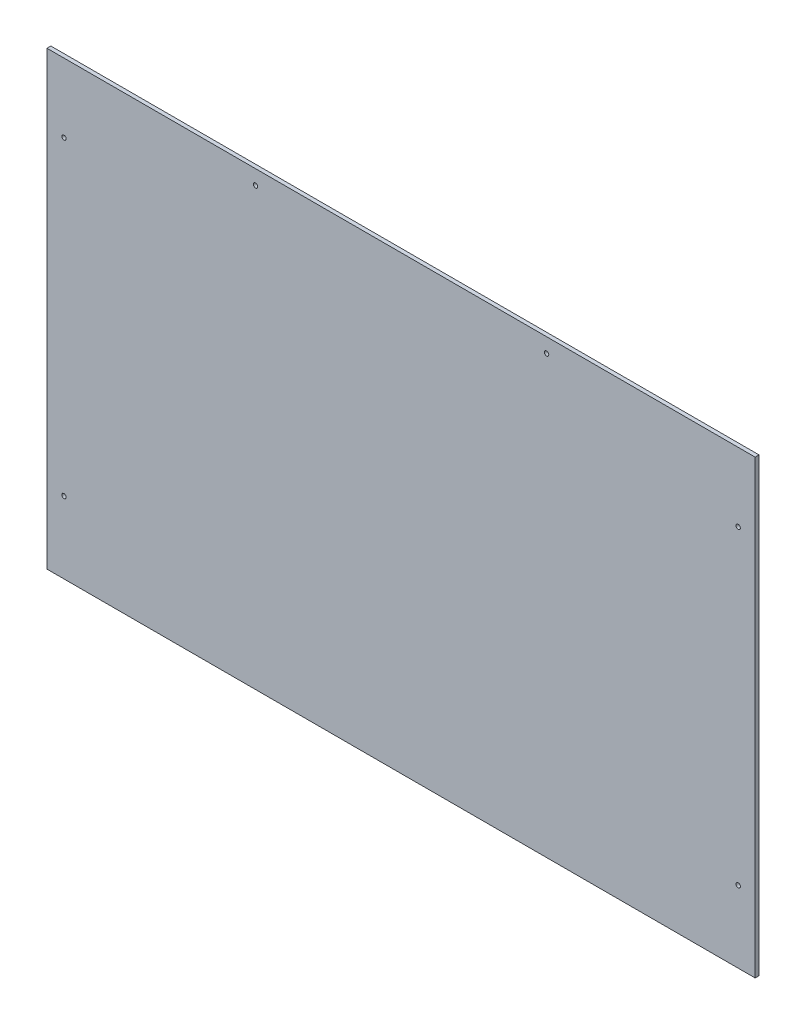
SolidWorks part; units mm, degrees
material "PC"
ref_plane "Front Plane" through (0, 0, 0) normal (0, 0, 1) x (1, 0, 0)
ref_plane "Top Plane" through (0, 0, 0) normal (0, 1, 0) x (1, 0, 0)
ref_plane "Right Plane" through (0, 0, 0) normal (1, 0, 0) x (0, 0, -1)
sketch "Sketch1" plane through (0, 0, 0) normal (0, 0, 1) x (1, 0, 0)
  line L1 (-365, 0) -> (365, 0)
  line L2 (-365, 0) -> (-365, -465)
  line L3 (-365, -465) -> (365, -465)
  line L4 (365, 0) -> (365, -465)
  dimension "D1" = 730
  dimension "D2" = 465
extrude "Boss-Extrude1" add sketch "Sketch1" along normal mid plane 4
sketch "Sketch2" plane through (0, 0, 2) normal (0, 0, 1) x (1, 0, 0)
  line L0 (150, -15) -> (-150, -15) construction
  line L1 (0, 0) -> (0, -15) construction
  line L2 (365, 0) -> (-365, 0) construction
  line L3 (-347.5, -391) -> (-347.5, -71) construction
  line L4 (-365, 0) -> (-365, -465) construction
  line L5 (-365, -465) -> (365, -465) construction
  circle A0 centre (-150, -15) radius 2.25
  circle A1 centre (150, -15) radius 2.25
  circle A2 centre (-347.5, -71) radius 2.25
  circle A3 centre (-347.5, -391) radius 2.25
  circle A4 centre (347.5, -391) radius 2.25
  circle A5 centre (347.5, -71) radius 2.25
  dimension "D1" = 300
  dimension "D2" = 4.5
  dimension "D4" = 17.5
  dimension "D5" = 71
  dimension "D3" = 15
  dimension "D6" = 74
extrude "Cut-Extrude1" cut sketch "Sketch2" against normal through all
